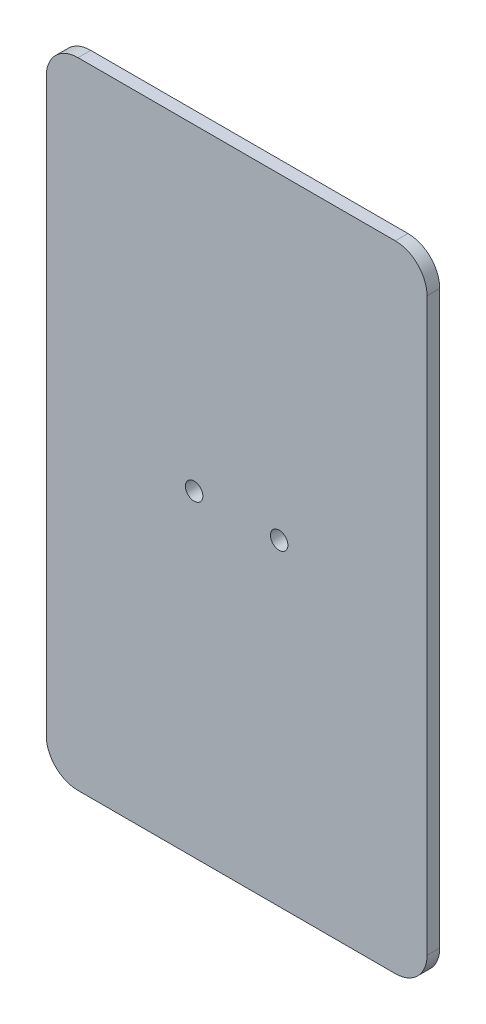
SolidWorks part; units mm, degrees
ref_plane "Front Plane" through (0, 0, 0) normal (0, 0, 1) x (1, 0, 0)
ref_plane "Top Plane" through (0, 0, 0) normal (0, 1, 0) x (1, 0, 0)
ref_plane "Right Plane" through (0, 0, 0) normal (1, 0, 0) x (0, 0, -1)
sketch "Sketch1" plane through (0, 0, 0) normal (0, 0, 1) x (1, 0, 0)
  line L0 (29.591, 63.5) -> (46.609, 63.5) construction
  line L1 (6.35, 0) -> (69.85, 0)
  line L2 (0, 6.35) -> (0, 120.65)
  line L3 (6.35, 127) -> (69.85, 127)
  line L4 (76.2, 6.35) -> (76.2, 120.65)
  arc A0 (6.35, 0) -> (0, 6.35) centre (6.35, 6.35) cw
  arc A1 (69.85, 0) -> (76.2, 6.35) centre (69.85, 6.35) ccw
  arc A2 (69.85, 127) -> (76.2, 120.65) centre (69.85, 120.65) cw
  arc A3 (0, 120.65) -> (6.35, 127) centre (6.35, 120.65) cw
  circle A4 centre (29.591, 63.5) radius 1.7462
  circle A5 centre (46.609, 63.5) radius 1.7462
  point P7 (0, 0)
  point P14 (0, 127)
  point P19 (38.1, 63.5)
  point P20 (0, 0)
  dimension "D3" = 6.35
  dimension "D5" = 63.5
  dimension "D7" = 3.4925
  dimension "D1" = 76.2
  dimension "D2" = 127
  dimension "D4" = 17.018
  dimension "D6" = 38.1
extrude "Boss-Extrude1" add sketch "Sketch1" along normal blind 2.54
